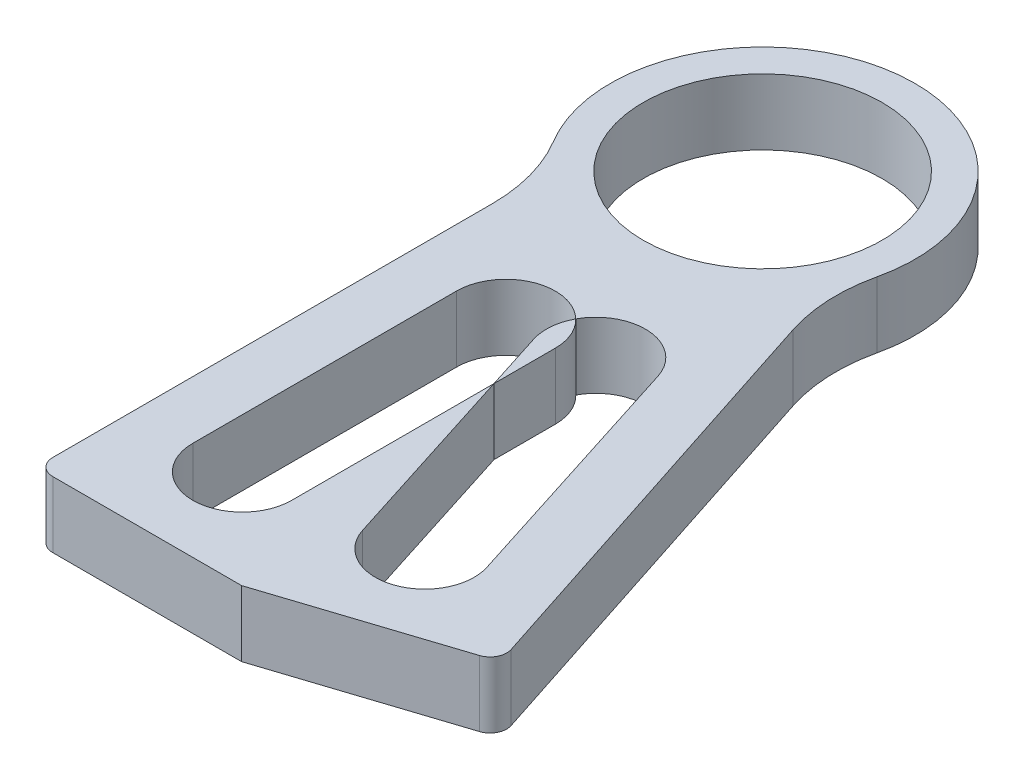
SolidWorks part; units mm, degrees
ref_plane "Front Plane" through (0, 0, 0) normal (0, 0, 1) x (1, 0, 0)
ref_plane "Top Plane" through (0, 0, 0) normal (0, 1, 0) x (1, 0, 0)
ref_plane "Right Plane" through (0, 0, 0) normal (1, 0, 0) x (0, 0, -1)
sketch "Sketch1" plane through (0, 0, 0) normal (0, 1, 0) x (1, 0, 0)
  line L0 (-10.3251, -10.437) -> (10.3251, -10.437)
  line L1 (0, -8.4388) -> (0, 23.3735) construction
  line L2 (-10.3251, -10.437) -> (-10.3251, -59.6596)
  line L3 (-10.3251, -59.6596) -> (10.3251, -59.6596)
  line L4 (10.3251, -59.6596) -> (10.3251, -10.437)
  line L5 (-6.59, -13.1191) -> (13.0473, -6.7309)
  line L6 (13.0473, -6.7309) -> (28.2743, -53.5392)
  line L7 (28.2743, -53.5392) -> (8.637, -59.9273)
  line L8 (8.637, -59.9273) -> (-6.59, -13.1191)
  line L9 (41.2176, -126.7041) -> (7.4103, -22.7796) construction
  circle A0 centre (0, 0) radius 11.5062
  circle A1 centre (0, 0) radius 14.6812
  point P7 (0, -10.437)
  point P16 (3.2287, -9.925)
  point P18 (18.4556, -56.7332)
  dimension "D1" = 23.0124
  dimension "D2" = 29.3624
  dimension "D3" = 20.6502
  dimension "D4" = 49.2227
  dimension "D5" = 18.02
  dimension "D6" = 20.6502
  dimension "D7" = 49.2227
extrude "Boss-Extrude1" add sketch "Sketch1" along normal blind 6.35 contours A1 L4 L8 L7 L6 | A1 L8 L4 | A1 L2 L3 L4 L8 | L0 A1 L5 A0 | L5 A1 L0 A0 | L0 A1 L5 A0 | L5 A1 L0 A0
fillet "Fillet1" radius 1.6002 2 edges at (-10.3251, 3.175, 59.6596) (28.2743, 3.175, 53.5392)
fillet "Fillet2" radius 15.875 2 edges at (13.0473, 3.175, 6.7309) (-10.3251, 3.175, 10.437)
sketch "Sketch2" plane through (0, 6.35, 0) normal (0, 1, 0) x (1, 0, 0)
  line L1 (20.153, -63.2732) -> (-1.545, 4.8507) construction
  line L2 (26.7526, -54.0342) -> (9.4598, -59.6596) construction
  line L3 (0, -64.2697) -> (0, 5.8755) construction
  line L4 (-4.7625, -50.1346) -> (-4.7625, -24.7346)
  line L5 (4.7625, -24.7346) -> (4.7625, -50.1346)
  line L6 (12.0443, -22.1222) -> (19.7529, -46.3243)
  line L7 (2.9686, -25.0129) -> (10.6771, -49.215)
  line L8 (-8.7249, -59.6596) -> (9.4598, -59.6596) construction
  circle A0 centre (15.215, -47.7696) radius 4.7625
  circle A1 centre (7.5065, -23.5676) radius 4.7625
  circle A2 centre (0, -24.7346) radius 4.7625
  circle A3 centre (0, -50.1346) radius 4.7625
  point P5 (18.1062, -56.8469)
  dimension "D1" = 9.525
  dimension "D2" = 25.4
  dimension "D3" = 25.4
  dimension "D4" = 9.525
  dimension "D5" = 9.5264
extrude "Cut-Extrude1" cut sketch "Sketch2" against normal blind 6.35 contours A2 | A3 L5 A2 L4 | A3 | A1 | A1 L7 A0 L6 | A0
